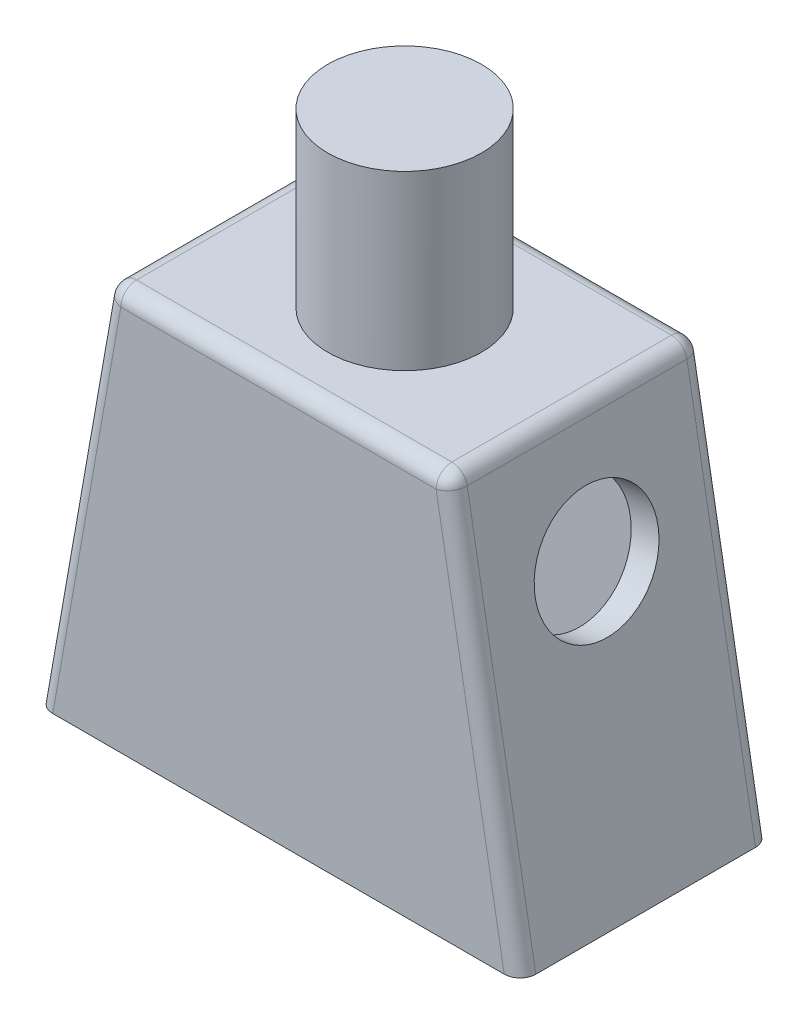
SolidWorks part; units mm, degrees
ref_plane "Front Plane" through (0, 0, 0) normal (0, 0, 1) x (1, 0, 0)
ref_plane "Top Plane" through (0, 0, 0) normal (0, 1, 0) x (1, 0, 0)
ref_plane "Right Plane" through (0, 0, 0) normal (1, 0, 0) x (0, 0, -1)
sketch "Sketch1" plane through (0, 0, 0) normal (0, 0, 1) x (1, 0, 0)
  line L0 (0, 0) -> (15.4, 0)
  line L1 (0, 0) -> (2.257, 12.8)
  line L2 (2.257, 12.8) -> (13.143, 12.8)
  line L3 (13.143, 12.8) -> (15.4, 0)
  dimension "D1" = 15.4
  dimension "D2" = 80
  dimension "D3" = 80
  dimension "D4" = 12.8
extrude "Boss-Extrude1" add sketch "Sketch1" along normal blind 8
sketch "Sketch5" plane through (0, 0, 8) normal (0, 0, 1) x (1, 0, 0)
  line L0 (1.1784, 0) -> (1.1784, 1.5)
  line L1 (0, 0) -> (15.4, 0) construction
  line L2 (1.1784, 1.5) -> (3.0122, 11.9)
  line L3 (3.0122, 11.9) -> (12.3878, 11.9)
  line L4 (12.3878, 11.9) -> (14.2216, 1.5)
  line L5 (14.2216, 1.5) -> (14.2216, 0)
  line L6 (2.257, 12.8) -> (0, 0) construction
  line L7 (15.4, 0) -> (13.143, 12.8) construction
  line L8 (1.1784, 0) -> (14.2216, 0)
  line L9 (13.143, 12.8) -> (2.257, 12.8) construction
  dimension "D1" = 1.5
  dimension "D2" = 1.5
  dimension "D3" = 0.9
  dimension "D4" = 0.9
  dimension "D5" = 0.9
extrude "Cut-Extrude3" cut sketch "Sketch5" against normal blind 5 from offset 1.5 offset against normal yes
ref_plane "Plane1" through (14.9356, 2.6336, 0) normal (0.9848, 0.1736, 0) x (0, 0, -1)
sketch "Sketch2" plane through (14.9356, 2.6336, 0) normal (0.9848, 0.1736, 0) x (0, 0, -1)
  line L0 (-8, -2.6742) -> (0, -2.6742) construction
  line L1 (-8, -2.6742) -> (-8, 10.3233) construction
  circle A0 centre (-4, 6.3258) radius 1.96
  dimension "D1" = 3.92
  dimension "D2" = 9
  dimension "D3" = 4
extrude "Cut-Extrude1" cut sketch "Sketch2" against normal blind 0.9
ref_plane "Plane2" through (0, 0, 0) normal (-0.9848, 0.1736, 0) x (0, 0, 1)
sketch "Sketch3" plane through (0, 0, 0) normal (-0.9848, 0.1736, 0) x (0, 0, 1)
  line L0 (0, 12.9975) -> (0, 0) construction
  line L1 (8, 0) -> (0, 0) construction
  circle A0 centre (4, 9) radius 2
  dimension "D1" = 4
  dimension "D2" = 4
  dimension "D3" = 9
extrude "Cut-Extrude2" cut sketch "Sketch3" against normal blind 0.9
fillet "Fillet1" radius 0.5 8 edges at (1.1285, 6.4, 0) (14.2715, 6.4, 0) (14.2715, 6.4, 8) (1.1285, 6.4, 8) (7.7, 12.8, 0) (13.143, 12.8, 4) (7.7, 12.8, 8) (2.257, 12.8, 4)
sketch "Sketch4" plane through (0, 12.8, 0) normal (0, 1, 0) x (1, 0, 0)
  line L0 (0, -7.5) -> (0, -0.5) construction
  line L2 (12.7235, -8) -> (2.6765, -8) construction
  circle A0 centre (7.72, -4) radius 2.45
  dimension "D1" = 4.9
  dimension "D2" = 7.72
  dimension "D3" = 4
extrude "Boss-Extrude2" add sketch "Sketch4" along normal blind 5.5
